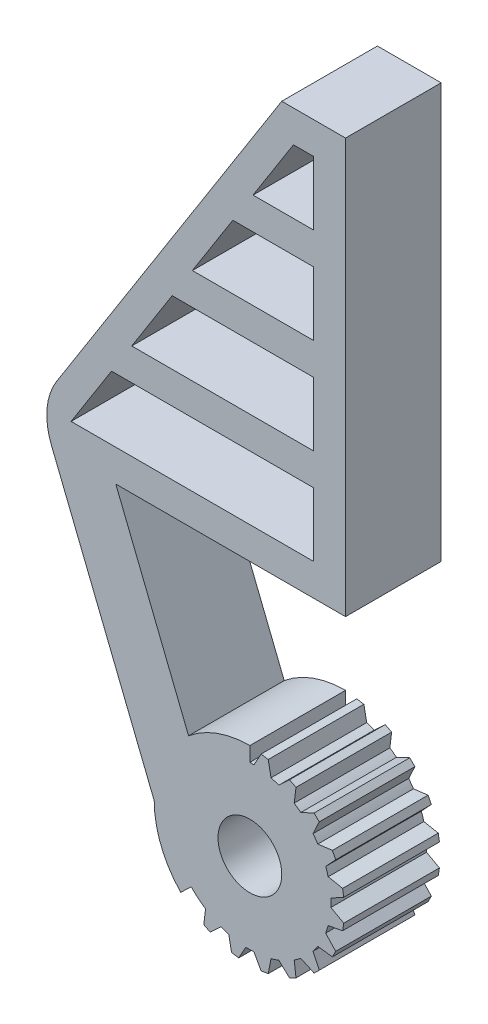
SolidWorks part; units mm, degrees
ref_plane "Front Plane" through (0, 0, 0) normal (0, 0, 1) x (1, 0, 0)
ref_plane "Top Plane" through (0, 0, 0) normal (0, 1, 0) x (1, 0, 0)
ref_plane "Right Plane" through (0, 0, 0) normal (1, 0, 0) x (0, 0, -1)
sketch "Sketch1" plane through (0, 0, 0) normal (0, 0, 1) x (1, 0, 0)
  line L0 (0, 0) -> (0, -120) construction
  line L1 (0, 0) -> (0, -10)
  line L2 (0, -50) -> (0, -60)
  line L5 (-48.033, -60) -> (-30, -105)
  line L7 (-36.0294, -65) -> (-20, -105)
  line L9 (-30, -105) -> (-20, -105)
  line L10 (0, 0) -> (0, -60)
  line L11 (-5, -60) -> (-43.033, -60)
  line L12 (0, 0) -> (-10, 0)
  line L13 (-8.1694, -5) -> (-14.5083, -15)
  line L14 (-5, -5) -> (-5, -15)
  line L15 (-5, -15) -> (-14.5083, -15)
  line L16 (-5, -20) -> (-5, -30)
  line L17 (-17.6777, -20) -> (-5, -20)
  line L18 (-24.0165, -30) -> (-5, -30)
  line L19 (-10, 0) -> (-48.033, -60)
  line L20 (-5, -50) -> (-5, -60)
  line L21 (-5, -35) -> (-27.1859, -35)
  line L22 (-33.5248, -45) -> (-5, -45)
  line L23 (-5, -5) -> (-8.1694, -5)
  line L24 (-5, -50) -> (-36.6942, -50)
  line L25 (0, -60) -> (0, -65)
  line L26 (0, -65) -> (-46.0294, -65)
  line L27 (-17.6777, -20) -> (-24.0165, -30)
  line L28 (-5, -35) -> (-5, -45)
  line L29 (-27.1859, -35) -> (-33.5248, -45)
  line L30 (-36.6942, -50) -> (-43.033, -60)
  circle A2 centre (-15, -105) radius 15
  circle A3 centre (-15, -105) radius 5
  point P27 (-9.7541, -15)
  dimension "D2" = 5
  dimension "D5" = 15
  dimension "D6" = 15
  dimension "D4" = 120
  dimension "D7" = 5
  dimension "D8" = 15
  dimension "D11" = 5
  dimension "D12" = 5
extrude "Boss-Extrude1" add sketch "Sketch1" along normal blind 15
sketch "Sketch2" plane through (0, 0, 15) normal (0, 0, 1) x (1, 0, 0)
  line L0 (-15, -90) -> (-15, -92.5)
  line L1 (-25.8458, -115.3619) -> (-24.0381, -113.6349)
  arc A0 (-25.8458, -115.3619) -> (-15, -90) centre (-15, -105) ccw
  arc A1 (-24.0381, -113.6349) -> (-15, -92.5) centre (-15, -105) ccw
  dimension "D1" = 2.5
  dimension "D2" = 30
extrude "Cut-Extrude1" cut sketch "Sketch2" against normal blind 15
sketch "Sketch3" plane through (0, 0, 15) normal (0, 0, 1) x (1, 0, 0)
  line L8 (-11.6824, -92.722) -> (-12.1222, -90.4558)
  line L9 (-13.2425, -90.2784) -> (-12.1222, -90.4558)
  line L10 (-14.3611, -92.2977) -> (-13.2425, -90.2784)
  line L12 (-8.0507, -94.3481) -> (-7.7686, -92.0569)
  line L13 (-8.7793, -91.542) -> (-7.7686, -92.0569)
  line L14 (-10.4672, -93.1168) -> (-8.7793, -91.542)
  line L16 (-5.0992, -97.0169) -> (-4.1229, -94.925)
  line L17 (-4.925, -94.1229) -> (-4.1229, -94.925)
  line L18 (-7.0169, -95.0992) -> (-4.925, -94.1229)
  line L20 (-3.1168, -100.4672) -> (-1.542, -98.7793)
  line L21 (-2.0569, -97.7686) -> (-1.542, -98.7793)
  line L22 (-4.3481, -98.0507) -> (-2.0569, -97.7686)
  line L24 (-2.2977, -104.3611) -> (-0.2784, -103.2425)
  line L25 (-0.4558, -102.1222) -> (-0.2784, -103.2425)
  line L26 (-2.722, -101.6824) -> (-0.4558, -102.1222)
  line L28 (-2.722, -108.3176) -> (-0.4558, -107.8778)
  line L29 (-0.2784, -106.7575) -> (-0.4558, -107.8778)
  line L30 (-2.2977, -105.6389) -> (-0.2784, -106.7575)
  line L32 (-4.3481, -111.9493) -> (-2.0569, -112.2314)
  line L33 (-1.542, -111.2207) -> (-2.0569, -112.2314)
  line L34 (-3.1168, -109.5328) -> (-1.542, -111.2207)
  line L36 (-7.0169, -114.9008) -> (-4.925, -115.8771)
  line L37 (-4.1229, -115.075) -> (-4.925, -115.8771)
  line L38 (-5.0992, -112.9831) -> (-4.1229, -115.075)
  line L40 (-10.4672, -116.8832) -> (-8.7793, -118.458)
  line L41 (-7.7686, -117.9431) -> (-8.7793, -118.458)
  line L42 (-8.0507, -115.6519) -> (-7.7686, -117.9431)
  line L44 (-14.3611, -117.7023) -> (-13.2425, -119.7216)
  line L45 (-12.1222, -119.5442) -> (-13.2425, -119.7216)
  line L46 (-11.6824, -117.278) -> (-12.1222, -119.5442)
  line L48 (-18.3176, -117.278) -> (-17.8778, -119.5442)
  line L49 (-16.7575, -119.7216) -> (-17.8778, -119.5442)
  line L50 (-15.6389, -117.7023) -> (-16.7575, -119.7216)
  line L52 (-21.9493, -115.6519) -> (-22.2314, -117.9431)
  line L53 (-21.2207, -118.458) -> (-22.2314, -117.9431)
  line L54 (-19.5328, -116.8832) -> (-21.2207, -118.458)
  line L94 (-12.6824, -90.3671) -> (-15, -105) construction
  line L95 (-8.274, -91.7994) -> (-15, -105) construction
  arc A0 (-10.4672, -93.1168) -> (-11.6824, -92.722) centre (-15, -105) ccw
  arc A1 (-14.3611, -92.2977) -> (-15.6389, -92.2977) centre (-15, -105) ccw
  arc A2 (-14.6378, -92.2868) -> (-21.9493, -115.6519) centre (-15, -105) ccw
  arc A3 (-7.0169, -95.0992) -> (-8.0507, -94.3481) centre (-15, -105) ccw
  arc A4 (-4.3481, -98.0507) -> (-5.0992, -97.0169) centre (-15, -105) ccw
  arc A5 (-2.722, -101.6824) -> (-3.1168, -100.4672) centre (-15, -105) ccw
  arc A6 (-2.2977, -105.6389) -> (-2.2977, -104.3611) centre (-15, -105) ccw
  arc A7 (-3.1168, -109.5328) -> (-2.722, -108.3176) centre (-15, -105) ccw
  arc A8 (-5.0992, -112.9831) -> (-4.3481, -111.9493) centre (-15, -105) ccw
  arc A9 (-8.0507, -115.6519) -> (-7.0169, -114.9008) centre (-15, -105) ccw
  arc A10 (-11.6824, -117.278) -> (-10.4672, -116.8832) centre (-15, -105) ccw
  arc A11 (-15.6389, -117.7023) -> (-14.3611, -117.7023) centre (-15, -105) ccw
  arc A12 (-19.5328, -116.8832) -> (-18.3176, -117.278) centre (-15, -105) ccw
  dimension "D2" = 18
extrude "Boss-Extrude2" add sketch "Sketch3" against normal blind 15
fillet "Fillet1" radius 10 1 edges at (-48.033, -60, 7.5)
